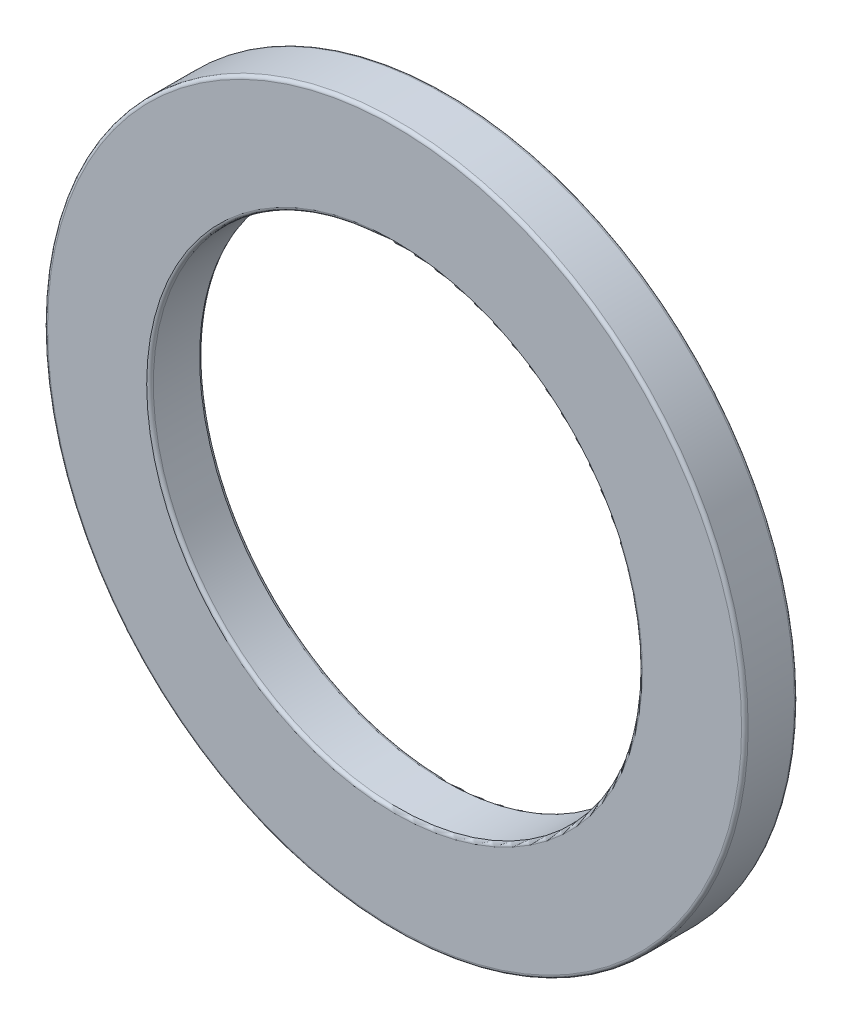
SolidWorks part; units mm, degrees
ref_plane "Спереди" through (0, 0, 0) normal (0, 0, 1) x (1, 0, 0)
ref_plane "Сверху" through (0, 0, 0) normal (0, 1, 0) x (1, 0, 0)
ref_plane "Справа" through (0, 0, 0) normal (1, 0, 0) x (0, 0, -1)
sketch "Эскиз1" plane through (0, 0, 0) normal (0, 0, 1) x (1, 0, 0)
  circle A0 centre (0, 0) radius 53
  circle A1 centre (0, 0) radius 37
  dimension "D1" = 106
  dimension "D2" = 74
extrude "Бобышка-Вытянуть1" add sketch "Эскиз1" along normal blind 8
fillet "Скругление1" radius 0.5 4 edges at (37, 0, 0) (37, 0, 8) (53, 0, 0) (53, 0, 8)
